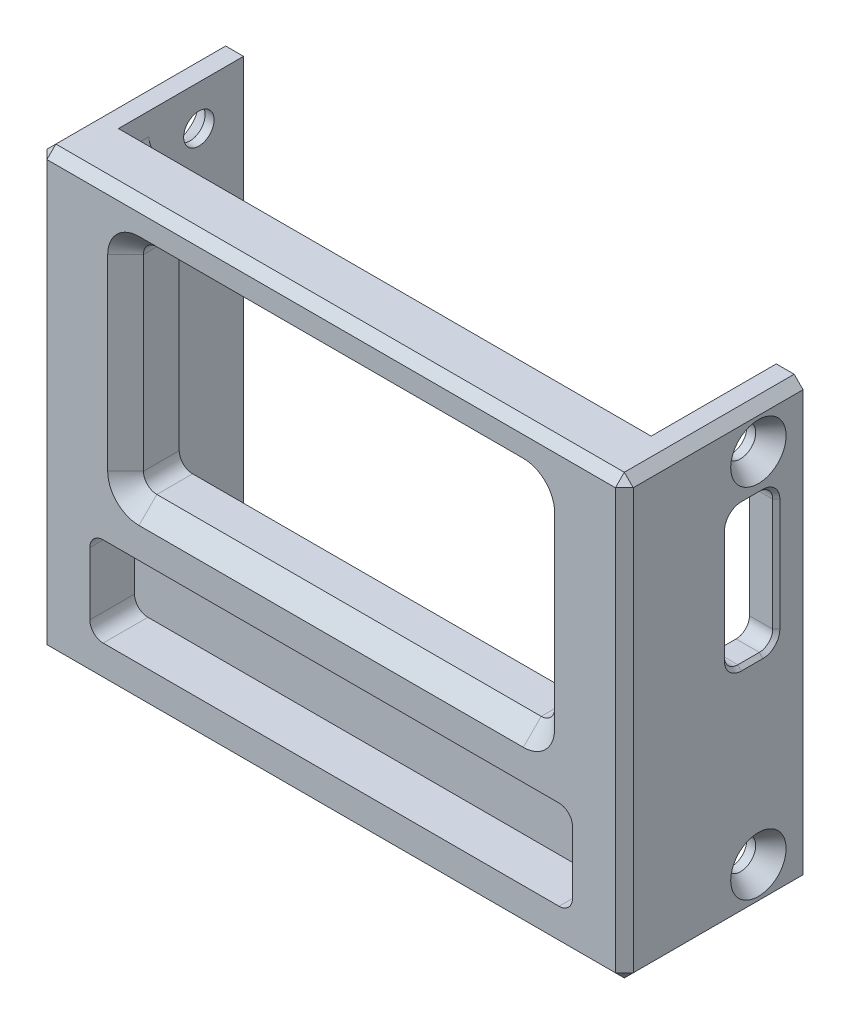
SolidWorks part; units mm, degrees
material "3003-H16"
ref_plane "Front Plane" through (0, 0, 0) normal (0, 0, 1) x (1, 0, 0)
ref_plane "Top Plane" through (0, 0, 0) normal (0, 1, 0) x (1, 0, 0)
ref_plane "Right Plane" through (0, 0, 0) normal (1, 0, 0) x (0, 0, -1)
sketch "Sketch1" plane through (0, 0, 0) normal (0, 0, 1) x (1, 0, 0)
  line L1 (-16.4, -12.25) -> (16.4, -12.25)
  line L2 (-16.4, -12.25) -> (-16.4, 12.25)
  line L3 (-16.4, 12.25) -> (16.4, 12.25)
  line L4 (16.4, -12.25) -> (16.4, 12.25)
  line L5 (-16.4, -12.25) -> (16.4, 12.25) construction
  line L6 (-16.4, 12.25) -> (16.4, -12.25) construction
  point P1 (0, 0)
  dimension "D1" = 32.8
  dimension "D2" = 24.5
extrude "Boss-Extrude1" add sketch "Sketch1" along normal blind 10
sketch "Sketch3" plane through (0, 0, 0) normal (0, 0, -1) x (-1, 0, 0)
  line L0 (-16.4, 12.25) -> (16.4, 12.25) construction
  line L1 (-14.9, -12.25) -> (14.9, -12.25)
  line L2 (-14.9, -12.25) -> (-14.9, 12.25)
  line L3 (-14.9, 12.25) -> (14.9, 12.25)
  line L4 (14.9, -12.25) -> (14.9, 12.25)
  line L5 (-14.9, -12.25) -> (14.9, 12.25) construction
  line L6 (-14.9, 12.25) -> (14.9, -12.25) construction
  point P0 (0, 0)
  dimension "D1" = 29.8
extrude "Cut-Extrude2" cut sketch "Sketch3" against normal blind 5.3
sketch "Sketch4" plane through (0, 0, 10) normal (0, 0, 1) x (1, 0, 0)
  line L0 (0, 12.25) -> (0, -12.25) construction
  line L1 (-10.75, -2.4) -> (10.75, -2.4)
  line L2 (-11.5, -1.65) -> (-11.5, 8.85)
  line L3 (-10.75, 9.6) -> (10.75, 9.6)
  line L4 (11.5, -1.65) -> (11.5, 8.85)
  line L5 (16.4, 12.25) -> (-16.4, 12.25) construction
  line L6 (-16.4, -12.25) -> (16.4, -12.25) construction
  arc A0 (-11.5, -1.65) -> (-10.75, -2.4) centre (-10.75, -1.65) ccw
  arc A1 (11.5, -1.65) -> (10.75, -2.4) centre (10.75, -1.65) cw
  arc A2 (10.75, 9.6) -> (11.5, 8.85) centre (10.75, 8.85) cw
  arc A3 (-10.75, 9.6) -> (-11.5, 8.85) centre (-10.75, 8.85) ccw
  point P11 (0, 9.6)
  point P14 (-11.5, -2.4)
  point P17 (11.5, -2.4)
  point P22 (-11.5, 9.6)
  dimension "D3" = 0.75
  dimension "D1" = 12
  dimension "D2" = 23
extrude "Cut-Extrude3" cut sketch "Sketch4" against normal through all
sketch "Sketch5" plane through (16.4, 0, 0) normal (1, 0, 0) x (0, 0, -1)
  line L1 (-3.45, 7.85) -> (-2.25, 7.85)
  line L2 (-4.2, 7.1) -> (-4.2, 0.8)
  line L3 (-3.45, 0.05) -> (-2.25, 0.05)
  line L4 (-1.5, 7.1) -> (-1.5, 0.8)
  arc A0 (-4.2, 0.8) -> (-3.45, 0.05) centre (-3.45, 0.8) ccw
  arc A1 (-2.25, 0.05) -> (-1.5, 0.8) centre (-2.25, 0.8) ccw
  arc A2 (-1.5, 7.1) -> (-2.25, 7.85) centre (-2.25, 7.1) ccw
  arc A3 (-3.45, 7.85) -> (-4.2, 7.1) centre (-3.45, 7.1) ccw
  point P6 (-4.2, 0.05)
  point P11 (-1.5, 7.85)
  point P14 (-4.2, 7.85)
  dimension "D3" = 0.75
  dimension "D1" = 7.8
  dimension "D2" = 2.7
extrude "Cut-Extrude4" cut sketch "Sketch5" against normal up to surface (1.5 mm away) contours L2 A0 L3 A1 L4 A2 L1 A3 up to face at (14.9, 0, 2.65)
chamfer "Chamfer1" distance 1 angle 45 8 edges at (0, -2.4, 10) (11.5, 3.6, 10) (0, 9.6, 10) (-11.5, 3.6, 10) (11.2803, 9.3803, 10) (11.2803, -2.1803, 10) (-11.2803, 9.3803, 10) (-11.2803, -2.1803, 10)
chamfer "Chamfer2" distance 0.2 angle 45 8 edges at (16.4, 0.05, 2.85) (16.4, 3.95, 1.5) (16.4, 3.95, 4.2) (16.4, 7.85, 2.85) (16.4, 0.2697, 3.9803) (16.4, 0.2697, 1.7197) (16.4, 7.6303, 3.9803) (16.4, 7.6303, 1.7197)
chamfer "Chamfer3" distance 0.5 angle 45 8 edges at (-16.4, 12.25, 5) (-16.4, -12.25, 5) (-16.4, 0, 10) (0, -12.25, 10) (16.4, -12.25, 5) (0, 12.25, 10) (16.4, 0, 10) (16.4, 12.25, 5)
sketch "Sketch8" plane through (0, 0, 10) normal (0, 0, 1) x (1, 0, 0)
  line L1 (-12.75, -10.1) -> (12.75, -10.1)
  line L2 (-13.5, -9.35) -> (-13.5, -5.85)
  line L3 (-12.75, -5.1) -> (12.75, -5.1)
  line L4 (13.5, -9.35) -> (13.5, -5.85)
  arc A0 (-13.5, -9.35) -> (-12.75, -10.1) centre (-12.75, -9.35) ccw
  arc A1 (12.75, -10.1) -> (13.5, -9.35) centre (12.75, -9.35) ccw
  arc A2 (13.5, -5.85) -> (12.75, -5.1) centre (12.75, -5.85) ccw
  arc A3 (-12.75, -5.1) -> (-13.5, -5.85) centre (-12.75, -5.85) ccw
  point P6 (-13.5, -10.1)
  point P14 (13.5, -5.1)
  point P17 (-13.5, -5.1)
  dimension "D3" = 0.75
  dimension "D1" = 27
  dimension "D2" = 5
extrude "Cut-Extrude6" cut sketch "Sketch8" against normal blind 2.5
sketch "Sketch9" plane through (16.4, 0, 0) normal (1, 0, 0) x (0, 0, -1)
  circle A0 centre (-2.5, -10) radius 0.85
  circle A1 centre (-2.5, 10) radius 0.85
  point P4 (0, 0)
sketch "Sketch10" plane through (-16.4, 0, 0) normal (-1, 0, 0) x (0, 0, 1)
  circle A0 centre (2.5, 10) radius 0.85
  circle A1 centre (2.5, -10) radius 0.85
extrude "Cut-Extrude7" cut sketch "Sketch10" against normal up to surface (1.5 mm away) up to face at (-14.9, 0, 2.65)
extrude "Cut-Extrude8" cut sketch "Sketch9" against normal up to surface (1.5 mm away) up to face at (14.9, 3.95, 2.85)
chamfer "Chamfer7" distance 0.7 angle 55 2 edges at (-16.4, -10, 3.35) (-16.4, 10, 3.35)
chamfer "Chamfer8" distance 0.7 angle 55 2 edges at (16.4, 10, 1.65) (16.4, -10, 1.65)
sketch "Sketch15" plane through (0, 0, 5.3) normal (0, 0, -1) x (-1, 0, 0)
  line L0 (-14.9, 12.25) -> (14.9, 12.25)
  line L1 (14.9, 12.25) -> (14.9, 11.0017)
  line L2 (14.9, -12.25) -> (14.9, 12.25) construction
  line L3 (14.15, 10.2517) -> (13.9005, 10.2517)
  line L4 (13.9005, 10.2517) -> (13.9005, -10.2463)
  line L5 (13.9005, -10.2463) -> (14.15, -10.2463)
  line L6 (14.9, -12.25) -> (14.9, 12.25) construction
  line L7 (14.9, -10.9963) -> (14.9, -12.25)
  line L8 (14.9, -12.25) -> (-14.9, -12.25)
  line L9 (-14.9, -12.25) -> (-14.9, -10.9963)
  line L10 (-14.9, 12.25) -> (-14.9, -12.25) construction
  line L11 (-14.15, -10.2463) -> (-13.9026, -10.2463)
  line L12 (-13.9026, -10.2463) -> (-13.9026, 10.2517)
  line L13 (-13.9026, 10.2517) -> (-14.15, 10.2517)
  line L14 (-14.9, 11.0017) -> (-14.9, 12.25)
  arc A0 (14.9, -10.9963) -> (14.15, -10.2463) centre (14.15, -10.9963) ccw
  arc A1 (14.9, 11.0017) -> (14.15, 10.2517) centre (14.15, 11.0017) cw
  arc A2 (-14.9, -10.9963) -> (-14.15, -10.2463) centre (-14.15, -10.9963) cw
  arc A3 (-14.9, 11.0017) -> (-14.15, 10.2517) centre (-14.15, 11.0017) ccw
  point P24 (14.9, -10.2463)
  point P27 (14.9, 10.2517)
  point P30 (-14.9, -10.2463)
  point P33 (-14.9, 10.2517)
  dimension "D1" = 0.75
extrude "Cut-Extrude11" cut sketch "Sketch15" against normal blind 1.7
